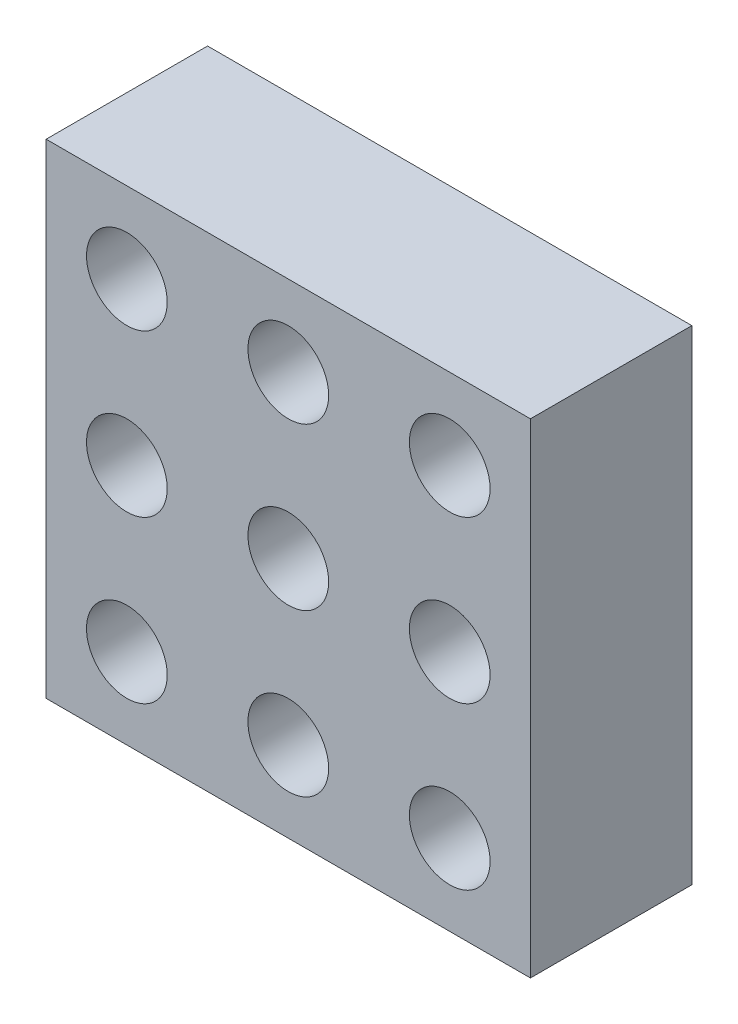
SolidWorks part; units mm, degrees
ref_plane "Front Plane" through (0, 0, 0) normal (0, 0, 1) x (1, 0, 0)
ref_plane "Top Plane" through (0, 0, 0) normal (0, 1, 0) x (1, 0, 0)
ref_plane "Right Plane" through (0, 0, 0) normal (1, 0, 0) x (0, 0, -1)
sketch "Sketch2" plane through (0, 0, 0) normal (0, 0, 1) x (1, 0, 0)
  line L1 (0, 0) -> (76.2, 0)
  line L2 (0, 0) -> (0, 76.2)
  line L3 (0, 76.2) -> (76.2, 76.2)
  line L4 (76.2, 0) -> (76.2, 76.2)
  dimension "D1" = 76.2
  dimension "D2" = 76.2
extrude "Boss-Extrude1" add sketch "Sketch2" along normal blind 25.4
sketch "Sketch3" plane through (0, 0, 25.4) normal (0, 0, 1) x (1, 0, 0)
  line L0 (0, 0) -> (76.2, 0) construction
  line L1 (0, 76.2) -> (0, 0) construction
  circle A0 centre (12.7, 12.7) radius 6.35
  dimension "D1" = 12.7
  dimension "D2" = 12.7
  dimension "D3" = 12.7
extrude "Cut-Extrude1" cut sketch "Sketch3" against normal through all
pattern_linear "LPattern1" count 3 spacing 25.4 along (0, 1, 0) count 3 spacing 25.4 along (1, 0, 0) of "Cut-Extrude1"
